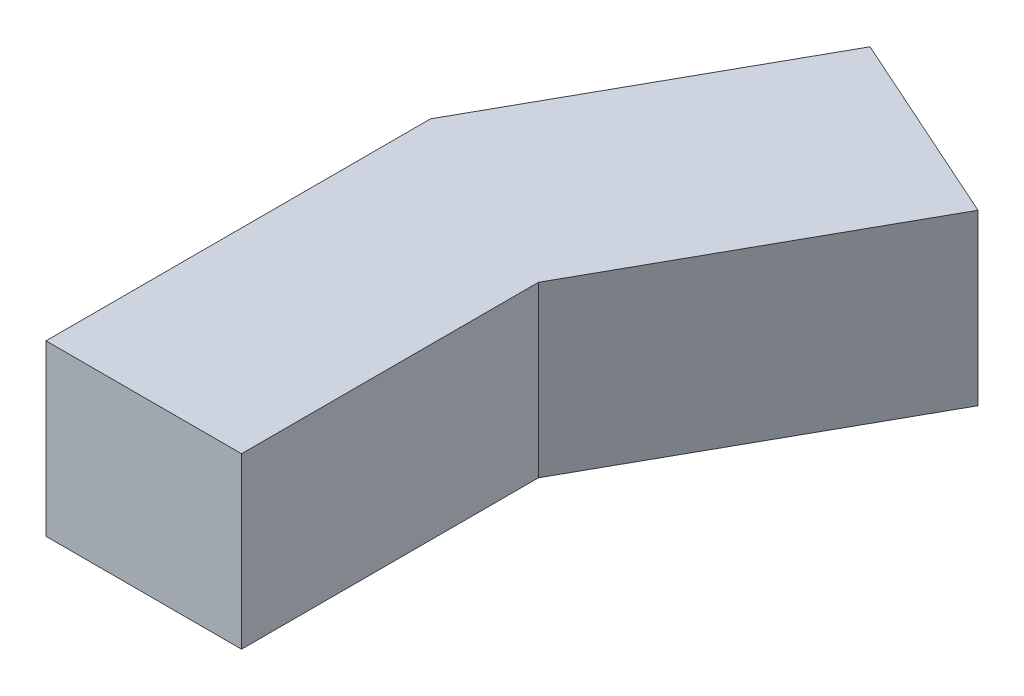
SolidWorks part; units mm, degrees
ref_plane "Front Plane" through (0, 0, 0) normal (0, 0, 1) x (1, 0, 0)
ref_plane "Top Plane" through (0, 0, 0) normal (0, 1, 0) x (1, 0, 0)
ref_plane "Right Plane" through (0, 0, 0) normal (1, 0, 0) x (0, 0, -1)
sketch "Sketch1" plane through (0, 0, 0) normal (0, 1, 0) x (1, 0, 0)
  line L0 (0, 32.246) -> (0, -11.0171)
  line L1 (11, -11.0171) -> (-11, -11.0171)
  line L2 (11, -11.0171) -> (11, 32.246)
  line L3 (11, 32.246) -> (-11, 32.246)
  line L4 (-11, -11.0171) -> (-11, 32.246)
  line L5 (-11, 32.246) -> (11, 22.3873)
  line L6 (-11, 32.246) -> (6.7066, 63.996)
  line L7 (11, 22.3873) -> (28.7066, 54.1373)
  line L8 (6.7066, 63.996) -> (28.7066, 54.1373)
  circle A0 centre (0, 0) radius 4.2724
  circle A1 centre (0, 20.1) radius 4.3133
  dimension "D1" = 20.1
  dimension "D2" = 22
  dimension "D3" = 31.75
extrude "Boss-Extrude1" add sketch "Sketch1" along normal blind 19.05 contours L8 L6 L3 L2 L7 | L0 L5 L2 L3 | A1 L0 A0 L1 L2 L5 | L3 L5 L0 | A1 L0 L5 L4 L1 A0 | L0 A1 | L0 A0 | L0 A0 | L0 A1
